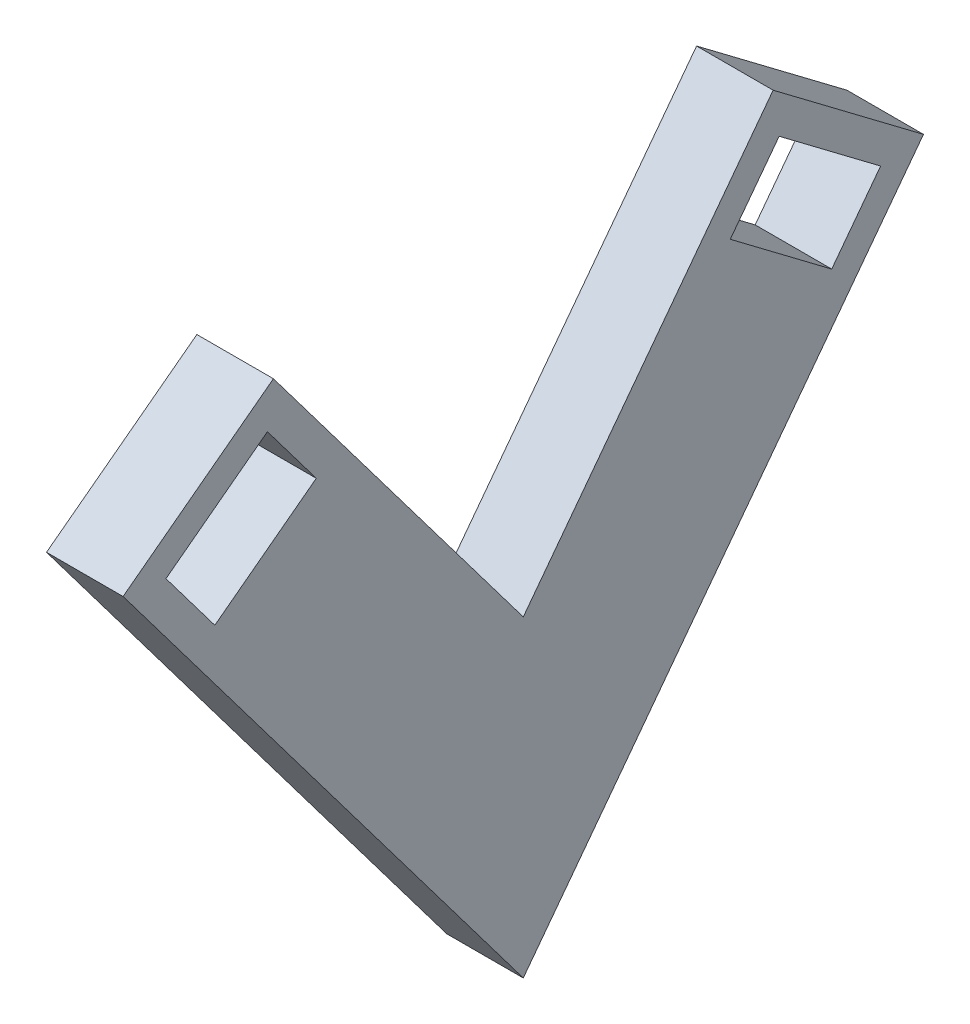
SolidWorks part; units mm, degrees
ref_plane "前视基准面" through (0, 0, 0) normal (0, 0, 1) x (1, 0, 0)
ref_plane "上视基准面" through (0, 0, 0) normal (0, 1, 0) x (1, 0, 0)
ref_plane "右视基准面" through (0, 0, 0) normal (1, 0, 0) x (0, 0, -1)
other "Configuration Table"
sketch "草图2" plane through (0, 0, 0) normal (1, 0, 0) x (0, 0, -1)
  line L0 (-18.4006, 10.0853) -> (-11.7745, 15.0838)
  line L5 (-11.7745, 15.0838) -> (-14.9664, 19.3149)
  line L6 (-14.9664, 19.3149) -> (-21.5924, 14.3164)
  line L7 (-21.5924, 14.3164) -> (-18.4006, 10.0853)
  line L8 (-18.2794, 16.8157) -> (-15.0876, 12.5846) construction
  line L9 (-19.9965, 12.2009) -> (-13.3705, 17.1994) construction
  line L10 (-16.6835, 14.7001) -> (32.3275, 14.7001) construction
  line L11 (-16.6835, 14.7001) -> (1.7448, -9.7285) construction
  dimension "D1" = 49.011
sketch "草图3" plane through (0, 0, 0) normal (1, 0, 0) x (0, 0, -1)
  line L0 (1.7448, 0.4835) -> (1.7448, -9.7285) construction
  line L1 (-14.5742, 22.116) -> (1.7448, 0.4835)
  line L2 (-11.7745, 15.0838) -> (-14.9664, 19.3149) construction
  line L3 (-14.5742, 22.116) -> (-24.3935, 14.7086)
  line L4 (-24.3935, 14.7086) -> (1.7448, -19.9405)
  line L5 (-21.5924, 14.3164) -> (-18.4006, 10.0853) construction
  line L6 (-14.9664, 19.3149) -> (-21.5924, 14.3164) construction
  line L7 (1.7448, -9.7285) -> (1.7448, -20.5282) construction
  line L8 (1.7448, 0.4835) -> (1.7448, -19.9405)
  dimension "D1" = 2
  dimension "D2" = 2
  dimension "D3" = 2
extrude "凸台-拉伸1" add sketch "草图3" along normal blind 5
extrude "切除-拉伸1" cut sketch "草图2" along normal blind 5
mirror "镜向1" about plane through (5, 0.4835, -1.7448) normal (0, 0, 1) of bodies 107
